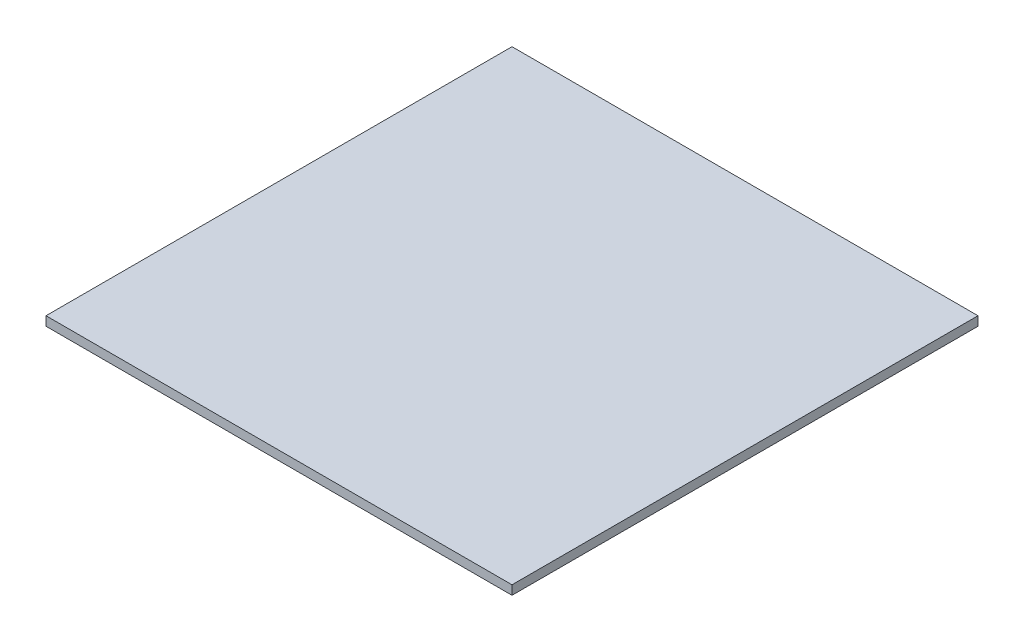
SolidWorks part; units mm, degrees
ref_plane "Front Plane" through (0, 0, 0) normal (0, 0, 1) x (1, 0, 0)
ref_plane "Top Plane" through (0, 0, 0) normal (0, 1, 0) x (1, 0, 0)
ref_plane "Right Plane" through (0, 0, 0) normal (1, 0, 0) x (0, 0, -1)
sketch "Sketch1" plane through (0, 0, 0) normal (0, 1, 0) x (1, 0, 0)
  line L1 (0, 0) -> (510, 0)
  line L2 (0, 0) -> (0, -510)
  line L3 (0, -510) -> (510, -510)
  line L4 (510, 0) -> (510, -510)
  dimension "D1" = 510
  dimension "D2" = 510
extrude "Boss-Extrude1" add sketch "Sketch1" along normal blind 10
